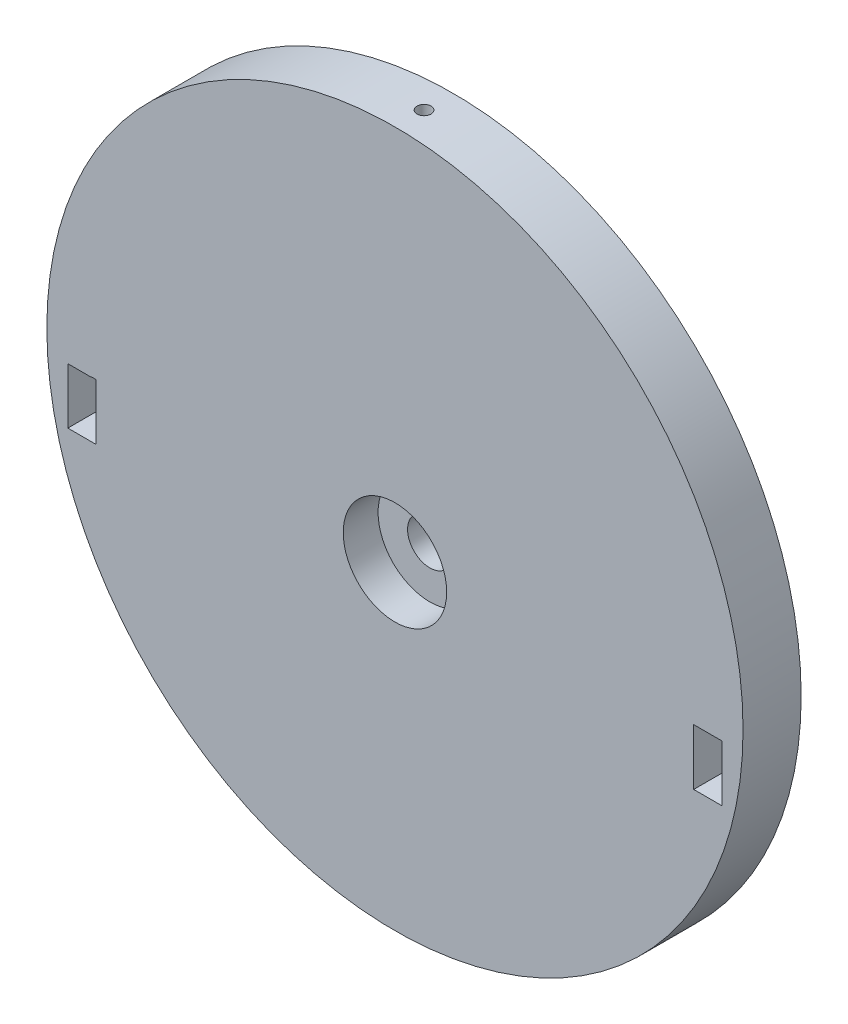
SolidWorks part; units mm, degrees
ref_plane "Front Plane" through (0, 0, 0) normal (0, 0, 1) x (1, 0, 0)
ref_plane "Top Plane" through (0, 0, 0) normal (0, 1, 0) x (1, 0, 0)
ref_plane "Right Plane" through (0, 0, 0) normal (1, 0, 0) x (0, 0, -1)
sketch "Sketch1" plane through (0, 0, 0) normal (0, 0, 1) x (1, 0, 0)
  circle A0 centre (0, 0) radius 76.073
  circle A1 centre (0, -6.35) radius 4.8641
  dimension "D1" = 152.146
  dimension "D2" = 9.7282
  dimension "D3" = 6.35
extrude "Boss-Extrude1" add sketch "Sketch1" along normal blind 12.7
sketch "Sketch2" plane through (0, 0, 12.7) normal (0, 0, 1) x (1, 0, 0)
  line L0 (0, 32.5625) -> (0, -27.8363) construction
  line L9 (71.484, -4.4196) -> (65.2864, -4.4196)
  line L10 (-73.406, 0) -> (-66.3574, 0)
  line L12 (-73.406, 0) -> (-73.406, -4.4958)
  line L13 (-73.406, -4.4958) -> (-66.3574, -4.4958)
  line L14 (-66.3574, 0) -> (-66.3574, -4.4958)
  line L16 (-73.406, -4.4958) -> (-66.3574, -4.4958)
  line L20 (-71.484, -16.6878) -> (-65.2864, -16.6878)
  line L21 (-71.484, -16.6878) -> (-71.484, -4.4196)
  line L22 (-71.484, -4.4196) -> (-65.2864, -4.4196)
  line L23 (-65.2864, -16.6878) -> (-65.2864, -4.4196)
  line L24 (65.2864, -16.6878) -> (65.2864, -4.4196)
  line L25 (71.484, -16.6878) -> (65.2864, -16.6878)
  line L26 (71.484, -16.6878) -> (71.484, -4.4196)
  circle A0 centre (0, 0) radius 73.406
  dimension "D1" = 146.812
  dimension "D2" = 4.4958
  dimension "D3" = 12.2682
  dimension "D4" = 6.1976
extrude "Cut-Extrude1" cut sketch "Sketch2" against normal through all contours L20 L23 L22 L16 L21 | L25 L26 L9 L24
sketch "Sketch3" plane through (0, 0, 12.7) normal (0, 0, 1) x (1, 0, 0)
  circle A0 centre (0, -6.35) radius 11.303
  dimension "D1" = 22.606
extrude "Cut-Extrude2" cut sketch "Sketch3" against normal blind 7.62
sketch "Sketch5" plane through (0, 0, 0) normal (0, 1, 0) x (1, 0, 0)
  circle A0 centre (0, -6.35) radius 1.524
  dimension "D2" = 3.048
  dimension "D1" = 6.35
extrude "Cut-Extrude3" cut sketch "Sketch5" against normal blind 6.35 from offset 76.073
sketch "Sketch6" plane through (0, 0, 0) normal (0, 1, 0) x (1, 0, 0)
  circle A0 centre (0, -6.35) radius 1.524
  dimension "D1" = 3.048
extrude "Cut-Extrude4" cut sketch "Sketch6" along normal blind 6.35 from offset 76.073 offset against normal yes
